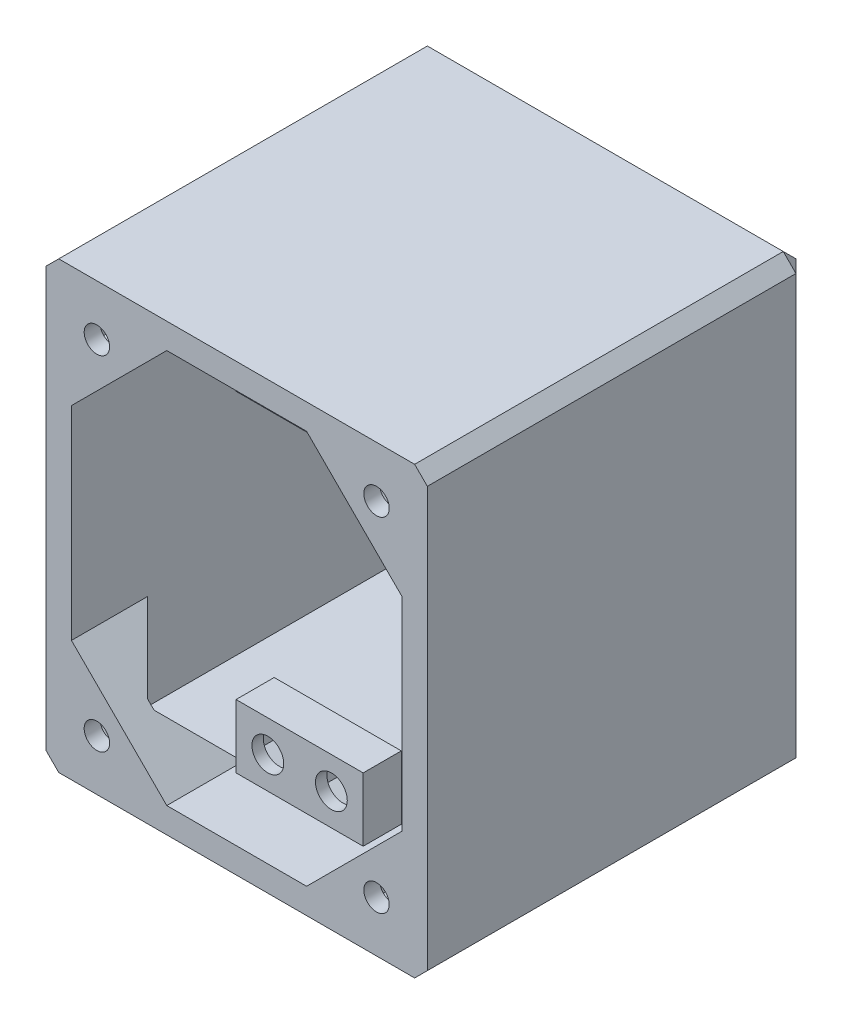
SolidWorks part; units mm, degrees
ref_plane "Ebene vorne" through (0, 0, 0) normal (0, 0, 1) x (1, 0, 0)
ref_plane "Ebene oben" through (0, 0, 0) normal (0, 1, 0) x (1, 0, 0)
ref_plane "Ebene rechts" through (0, 0, 0) normal (1, 0, 0) x (0, 0, -1)
sketch "Skizze1" plane through (0, 0, 0) normal (0, 0, 1) x (1, 0, 0)
  line L1 (0, 0) -> (60, 0)
  line L2 (0, 0) -> (0, 70)
  line L3 (0, 70) -> (60, 70)
  line L4 (60, 0) -> (60, 70)
  dimension "D1" = 60
  dimension "D2" = 70
extrude "Grundkörper" add sketch "Skizze1" along normal blind 60
chamfer "Fase2" distance 2 angle 45 7 edges at (0, 0, 30) (60, 0, 30) (60, 70, 30) (0, 70, 30) (0, 35, 0) (30, 70, 0) (60, 35, 0)
shell "Wandung1" thickness 4
sketch "Skizze2" plane through (0, 4, 0) normal (0, 1, 0) x (1, 0, 0)
  line L5 (30, -60) -> (30, -4) construction
  line L6 (4, -60) -> (56, -60) construction
  line L7 (4, -4) -> (56, -4) construction
  line L12 (40, -50.1) -> (20, -50.1)
  line L13 (20, -50.1) -> (20, -44.1)
  line L14 (20, -44.1) -> (40, -44.1)
  line L15 (58, -60) -> (2, -60) construction
  line L16 (40, -50.1) -> (40, -44.1)
  point P13 (30, -44.1)
  point P14 (30, -50.1)
  dimension "D1" = 9.9
  dimension "D2" = 6
  dimension "D3" = 20
extrude "Aufsatz-Linear austragen1" add sketch "Skizze2" along normal blind 10 contours L14 L16 L12 L13
ref_plane "Ebene1" through (0, 35, 0) normal (0, -1, 0) x (-1, 0, 0)
mirror "Spiegeln1" about plane through (0, 35, 0) normal (0, -1, 0) of "Aufsatz-Linear austragen1"
sketch "Skizze3" plane through (0, 0, 50.1) normal (0, 0, 1) x (1, 0, 0)
  line L0 (40, 14) -> (40, 4) construction
  line L2 (40, 4) -> (20, 4) construction
  line L3 (4, 4) -> (56, 4) construction
  line L4 (-28.6, 35) -> (28.6, 35) construction
  circle A0 centre (25, 9) radius 2.5
  circle A1 centre (35, 9) radius 2.5
  circle A2 centre (35, 61) radius 2.5
  circle A3 centre (25, 61) radius 2.5
  dimension "D3" = 5
  dimension "D4" = 5
  dimension "D1" = 10
  dimension "D2" = 5
  dimension "D5" = 5
  dimension "D6" = 5
extrude "Bohrungen Servo" cut sketch "Skizze3" against normal up to next
sketch "Skizze5" plane through (0, 0, 44.1) normal (0, 0, -1) x (-1, 0, 0)
  line L0 (-28.6, 35) -> (28.6, 35) construction
  line L1 (-34.9787, 13.0414) -> (-38.4893, 11.0392)
  line L2 (-38.4893, 11.0392) -> (-38.5106, 6.9978)
  line L3 (-38.5106, 6.9978) -> (-35.0213, 4.9586)
  line L4 (-35.0213, 4.9586) -> (-31.5107, 6.9608)
  line L5 (-31.5107, 6.9608) -> (-31.4894, 11.0022)
  line L6 (-31.4894, 11.0022) -> (-34.9787, 13.0414)
  line L7 (-31.4894, 58.9978) -> (-34.9787, 56.9586)
  line L8 (-31.5107, 63.0392) -> (-31.4894, 58.9978)
  line L9 (-35.0213, 65.0414) -> (-31.5107, 63.0392)
  line L10 (-38.5106, 63.0022) -> (-35.0213, 65.0414)
  line L11 (-38.4893, 58.9608) -> (-38.5106, 63.0022)
  line L12 (-34.9787, 56.9586) -> (-38.4893, 58.9608)
  line L13 (-30, 0) -> (-30, 70) construction
  line L14 (-2, 0) -> (-58, 0) construction
  line L15 (-58, 70) -> (-2, 70) construction
  line L16 (-28.4893, 63.0392) -> (-28.5106, 58.9978)
  line L17 (-24.9787, 65.0414) -> (-28.4893, 63.0392)
  line L18 (-21.4894, 63.0022) -> (-24.9787, 65.0414)
  line L19 (-21.5107, 58.9608) -> (-21.4894, 63.0022)
  line L20 (-25.0213, 56.9586) -> (-21.5107, 58.9608)
  line L21 (-28.5106, 58.9978) -> (-25.0213, 56.9586)
  line L22 (-28.5106, 11.0022) -> (-25.0213, 13.0414)
  line L23 (-25.0213, 13.0414) -> (-21.5107, 11.0392)
  line L24 (-21.5107, 11.0392) -> (-21.4894, 6.9978)
  line L25 (-21.4894, 6.9978) -> (-24.9787, 4.9586)
  line L26 (-24.9787, 4.9586) -> (-28.4893, 6.9608)
  line L27 (-28.4893, 6.9608) -> (-28.5106, 11.0022)
  circle A0 centre (-35, 9) radius 3.5 construction
  circle A1 centre (-35, 9) radius 2.5
  circle A2 centre (-25, 9) radius 2
  circle A3 centre (-25, 61) radius 2.5
  circle A4 centre (-35, 61) radius 2.5
  dimension "D2" = 4
  dimension "D1" = 7
extrude "Sechskant" cut sketch "Skizze5" against normal blind 4.2
sketch "Skizze7" plane through (0, 0, 60) normal (0, 0, 1) x (1, 0, 0)
  line L0 (56, 4) -> (41, 4)
  line L1 (4, 4) -> (56, 4) construction
  line L2 (41, 4) -> (56, 19)
  line L3 (56, 4) -> (56, 66) construction
  line L4 (56, 19) -> (56, 4)
  line L5 (30, 4) -> (30, 66) construction
  line L6 (40, 4) -> (20, 4) construction
  line L7 (56, 66) -> (4, 66) construction
  line L8 (19, 4) -> (4, 19)
  line L9 (4, 4) -> (19, 4)
  line L10 (4, 19) -> (4, 4)
  line L11 (-28.6, 35) -> (28.6, 35) construction
  line L12 (4, 66) -> (19, 66)
  line L13 (4, 51) -> (4, 66)
  line L14 (19, 66) -> (4, 51)
  line L15 (41, 66) -> (56, 51)
  line L16 (56, 66) -> (41, 66)
  line L17 (56, 51) -> (56, 66)
  dimension "D1" = 15
  dimension "D2" = 15
extrude "Ausparungen" add sketch "Skizze7" against normal blind 5
chamfer "Fase3" distance 7 angle 45 8 edges at (56, 58.5, 55) (48.5, 66, 55) (56, 11.5, 55) (48.5, 4, 55) (11.5, 66, 55) (4, 58.5, 55) (11.5, 4, 55) (4, 11.5, 55)
sketch "Skizze8" plane through (0, 0, 60) normal (0, 0, 1) x (1, 0, 0)
  line L0 (58, 0) -> (58, 70) construction
  line L1 (60, 2) -> (0, 2) construction
  line L2 (0, 2) -> (2, 0) construction
  line L3 (2, 0) -> (2, 70) construction
  line L4 (30, 0) -> (30, 70) construction
  line L5 (2, 0) -> (58, 0) construction
  line L6 (58, 70) -> (2, 70) construction
  line L7 (-28.6, 35) -> (28.6, 35) construction
  circle A0 centre (52, 8) radius 2
  circle A1 centre (8, 8) radius 2
  circle A2 centre (8, 62) radius 2
  circle A3 centre (52, 62) radius 2
  dimension "D1" = 4
  dimension "D2" = 6
  dimension "D3" = 6
extrude "BohrungenHalterung" cut sketch "Skizze8" against normal up to next
ref_plane "Ebene2" through (0, 0, 57.5) normal (0, 0, 1) x (1, 0, 0)
sketch "Skizze13" plane through (0, 0, 57.5) normal (0, 0, 1) x (1, 0, 0)
  line L0 (41, 66) -> (56, 51) construction
  line L1 (50.9092, 57.929) -> (54.9802, 59.0198)
  line L2 (54.9802, 59.0198) -> (56.071, 63.0908)
  line L3 (56.071, 63.0908) -> (53.0908, 66.071)
  line L4 (53.0908, 66.071) -> (49.0198, 64.9802)
  line L5 (49.0198, 64.9802) -> (47.929, 60.9092)
  line L6 (47.929, 60.9092) -> (50.9092, 57.929)
  line L7 (49.0198, 5.0198) -> (53.0908, 3.929)
  line L8 (53.0908, 3.929) -> (56.071, 6.9092)
  line L9 (56.071, 6.9092) -> (54.9802, 10.9802)
  line L10 (54.9802, 10.9802) -> (50.9092, 12.071)
  line L11 (50.9092, 12.071) -> (47.929, 9.0908)
  line L12 (47.929, 9.0908) -> (49.0198, 5.0198)
  line L13 (3.929, 6.9092) -> (6.9092, 3.929)
  line L14 (6.9092, 3.929) -> (10.9802, 5.0198)
  line L15 (10.9802, 5.0198) -> (12.071, 9.0908)
  line L16 (12.071, 9.0908) -> (9.0908, 12.071)
  line L17 (9.0908, 12.071) -> (5.0198, 10.9802)
  line L18 (5.0198, 10.9802) -> (3.929, 6.9092)
  line L19 (5.0198, 59.0198) -> (9.0908, 57.929)
  line L20 (9.0908, 57.929) -> (12.071, 60.9092)
  line L21 (12.071, 60.9092) -> (10.9802, 64.9802)
  line L22 (10.9802, 64.9802) -> (6.9092, 66.071)
  line L23 (6.9092, 66.071) -> (3.929, 63.0908)
  line L24 (3.929, 63.0908) -> (5.0198, 59.0198)
  line L25 (56, 19) -> (41, 4) construction
  line L26 (19, 4) -> (4, 19) construction
  line L27 (4, 51) -> (19, 66) construction
  circle A0 centre (52, 62) radius 3.65 construction
  circle A1 centre (52, 8) radius 3.65 construction
  circle A2 centre (8, 8) radius 3.65 construction
  circle A3 centre (8, 62) radius 3.65 construction
  dimension "D1" = 7.3
extrude "Sechskant Deckel" cut sketch "Skizze13" against normal up to vertex (7.4 mm away)
sketch "Skizze11" plane through (0, 0, 0) normal (0, 0, -1) x (-1, 0, 0)
  line L0 (-28.6, 35) -> (28.6, 35) construction
  line L1 (-2, 0) -> (-2, 68) construction
  circle A1 centre (-30, 35) radius 3
  dimension "D4" = 6
  dimension "D1" = 28
extrude "Bohrung Verschraubung Deckel" cut sketch "Skizze11" against normal up to next
sketch "Skizze14" plane through (0, 0, 0) normal (0, 0, -1) x (-1, 0, 0)
  line L1 (-36, 20) -> (-24, 20)
  line L2 (-36, 20) -> (-36, 40)
  line L3 (-36, 40) -> (-24, 40)
  line L4 (-24, 20) -> (-24, 40)
  circle A0 centre (-30, 35) radius 0.8839
  dimension "D1" = 20
  dimension "D2" = 12
  dimension "D3" = 6
  dimension "D4" = 15
extrude "Vertiefung Deckel" cut sketch "Skizze14" against normal blind 2
